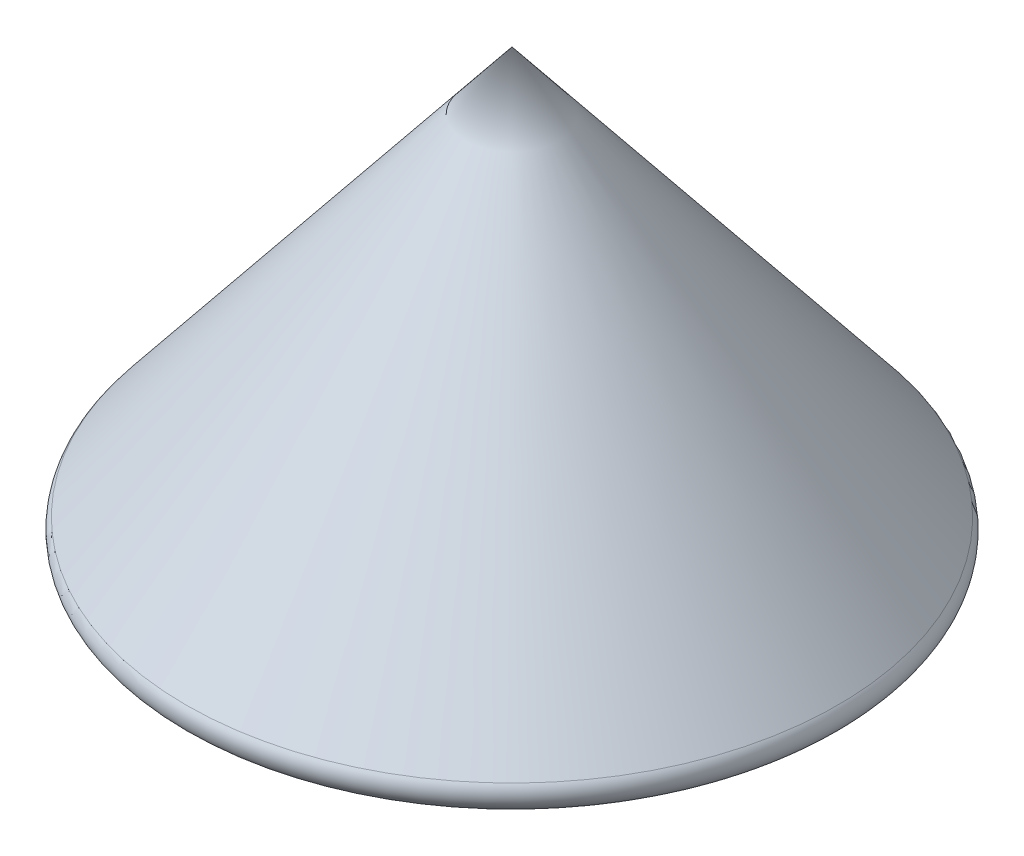
SolidWorks part; units mm, degrees
ref_plane "Front Plane" through (0, 0, 0) normal (0, 0, 1) x (1, 0, 0)
ref_plane "Top Plane" through (0, 0, 0) normal (0, 1, 0) x (1, 0, 0)
ref_plane "Right Plane" through (0, 0, 0) normal (1, 0, 0) x (0, 0, -1)
sketch "Sketch1" plane through (0, 0, 0) normal (0, 0, 1) x (1, 0, 0)
  line L0 (0, 0) -> (20, 0)
  line L1 (20, 0) -> (0, 25)
  line L2 (0, 25) -> (0, 0)
  line L3 (0, 25) -> (0, -18.4411) construction
  dimension "D1" = 25
  dimension "D2" = 20
revolve "Revolve1" add sketch "Sketch1" angle 360 about L3
sketch "Sketch2" plane through (0, 0, 0) normal (0, -1, 0) x (1, 0, 0)
  circle A0 centre (0, 0) radius 2.9
extrude "Cut-Extrude1" cut sketch "Sketch2" against normal blind 13
fillet "Fillet1" radius 1 1 edges at (0, 0, 20)
